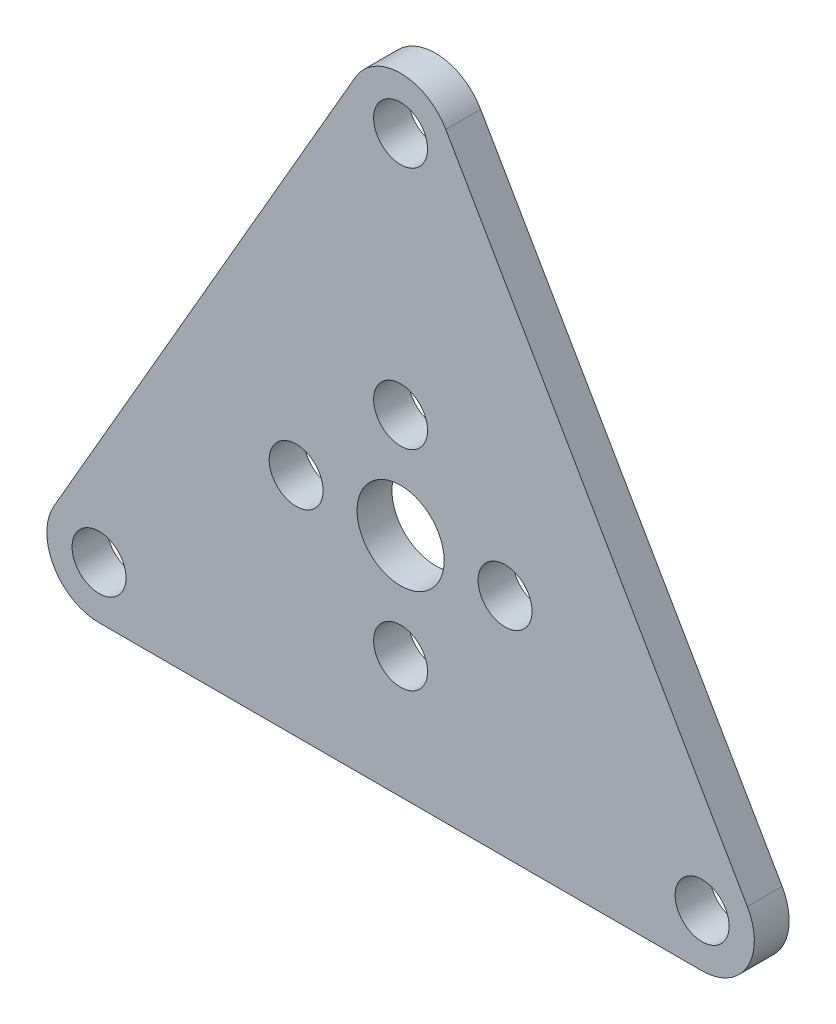
SolidWorks part; units mm, degrees
material "Thornel Mat VMA"
ref_plane "前视基准面" through (0, 0, 0) normal (0, 0, 1) x (1, 0, 0)
ref_plane "上视基准面" through (0, 0, 0) normal (0, 1, 0) x (1, 0, 0)
ref_plane "右视基准面" through (0, 0, 0) normal (1, 0, 0) x (0, 0, -1)
sketch "草图1" plane through (0, 0, 0) normal (0, 0, 1) x (1, 0, 0)
  line L0 (0, 0) -> (0, 20) construction
  line L1 (0, 0) -> (17.3205, -10) construction
  line L2 (-2.5981, 21.5) -> (-19.9186, -8.5)
  line L3 (-17.3205, -13) -> (17.3205, -13)
  line L4 (2.5981, 21.5) -> (19.9186, -8.5)
  circle A0 centre (0, 0) radius 20 construction
  circle A1 centre (0, 20) radius 1.55
  arc A2 (2.5981, 21.5) -> (-2.5981, 21.5) centre (0, 20) ccw
  circle A3 centre (17.3205, -10) radius 1.55
  arc A4 (17.3205, -13) -> (19.9186, -8.5) centre (17.3205, -10) ccw
  circle A5 centre (-17.3205, -10) radius 1.55
  arc A6 (-19.9186, -8.5) -> (-17.3205, -13) centre (-17.3205, -10) ccw
  dimension "D1" = 40
  dimension "D2" = 3.1
  dimension "D3" = 6
  dimension "D5" = 120
  dimension "D4" = 3
extrude "凸台-拉伸1" add sketch "草图1" along normal blind 2
sketch "草图2" plane through (0, 0, 2) normal (0, 0, 1) x (1, 0, 0)
  circle A0 centre (0, 0) radius 9 construction
  circle A1 centre (0, 0) radius 6 construction
  circle A2 centre (0, 6) radius 1.55
  circle A3 centre (6, 0) radius 1.55
  circle A4 centre (0, -6) radius 1.55
  circle A5 centre (-6, 0) radius 1.55
  dimension "D1" = 18
  dimension "D3" = 3.1
  dimension "D2" = 3
extrude "切除-拉伸1" cut sketch "草图2" against normal blind 3
sketch "草图4" plane through (0, 0, 2) normal (0, 0, 1) x (1, 0, 0)
  circle A0 centre (0, 0) radius 2.5
  dimension "D1" = 5
extrude "切除-拉伸2" cut sketch "草图4" against normal blind 3
